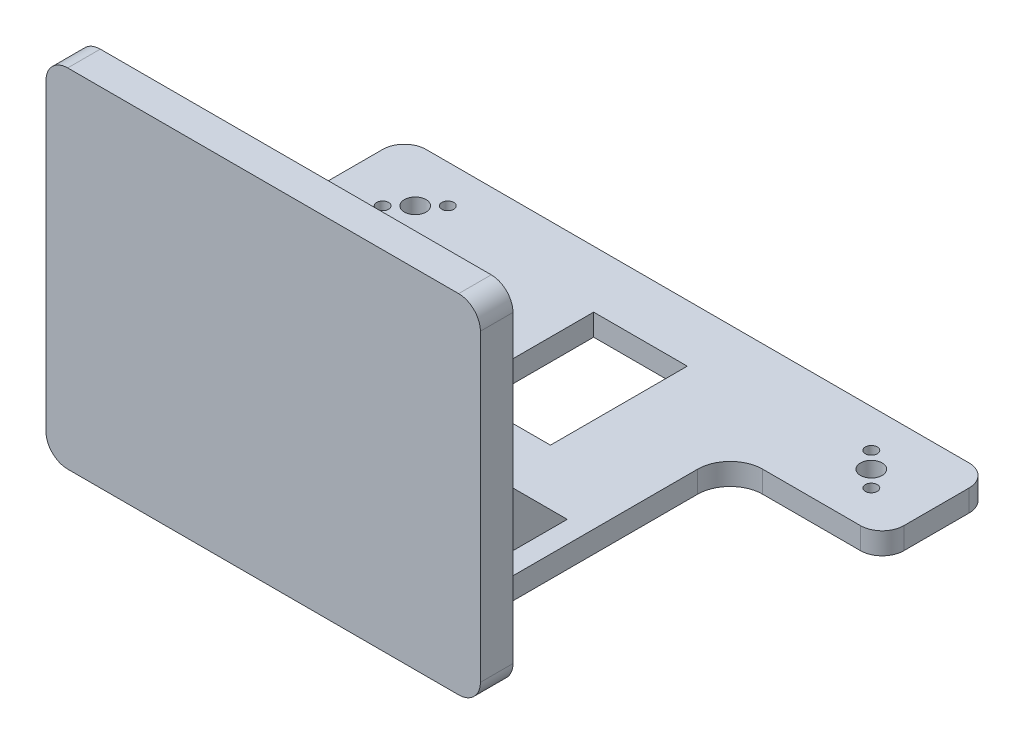
SolidWorks part; units mm, degrees
ref_plane "Vorne" through (0, 0, 0) normal (0, 0, 1) x (1, 0, 0)
ref_plane "Oben" through (0, 0, 0) normal (0, 1, 0) x (1, 0, 0)
ref_plane "Rechts" through (0, 0, 0) normal (1, 0, 0) x (0, 0, -1)
ref_plane "E_Boden" through (0, 1, 0) normal (0, 1, 0) x (1, 0, 0)
sketch "Skizze1" plane through (0, 0, 0) normal (0, 1, 0) x (1, 0, 0)
  line L0 (0, -133.037) -> (0, 127.1868) construction
  line L1 (-165.4867, 0) -> (188.3198, 0) construction
  line L2 (-125, 100) -> (125, 100)
  line L3 (-135, 90) -> (-135, 60)
  line L8 (-125, 50) -> (-80, 50)
  line L9 (-65, 35) -> (-65, -70)
  line L10 (-80, -85) -> (-90, -85)
  line L12 (-80, -100) -> (80, -100)
  line L14 (80, -85) -> (90, -85)
  line L15 (65, 35) -> (65, -70)
  line L16 (125, 50) -> (80, 50)
  line L17 (135, 90) -> (135, 60)
  line L18 (0, 75) -> (-166.9097, 75) construction
  line L19 (0, 82.5) -> (-150.2601, 82.5) construction
  line L20 (0, 67.5) -> (-143.7021, 67.5) construction
  line L21 (-112.5, 67.5) -> (-112.5, 109.8946) construction
  line L22 (-97.5, 82.5) -> (-97.5, 110.5565) construction
  line L23 (-105, 75) -> (-105, 35) construction
  line L24 (-105, 35) -> (-105, 140.5126) construction
  line L25 (-21.55, 73.71) -> (21.55, 73.71)
  line L26 (21.55, 73.71) -> (21.55, 10.71)
  line L27 (21.55, 10.71) -> (-21.55, 10.71)
  line L28 (-21.55, 10.71) -> (-21.55, 73.71)
  line L29 (0, 42.21) -> (-56.3168, 42.21) construction
  line L30 (-56.3168, 42.21) -> (55.721, 42.21) construction
  line L32 (-100, -100) -> (-80, -100)
  line L33 (80, -100) -> (100, -100)
  line L35 (-90, -85) -> (-100, -85)
  line L37 (90, -85) -> (100, -85)
  line L39 (-100, -85) -> (-100, -100)
  line L40 (100, -85) -> (100, -100)
  arc A0 (65, 35) -> (80, 50) centre (80, 35) cw
  arc A1 (80, -85) -> (65, -70) centre (80, -70) cw
  arc A2 (-65, -70) -> (-80, -85) centre (-80, -70) cw
  arc A3 (-80, 50) -> (-65, 35) centre (-80, 35) cw
  arc A8 (-135, 60) -> (-125, 50) centre (-125, 60) ccw
  arc A9 (125, 50) -> (135, 60) centre (125, 60) ccw
  arc A10 (135, 90) -> (125, 100) centre (125, 90) ccw
  arc A11 (-125, 100) -> (-135, 90) centre (-125, 90) ccw
  circle A12 centre (-105, 75) radius 5
  circle A13 centre (105, 75) radius 5
  circle A14 centre (-97.5, 82.5) radius 2.75
  circle A15 centre (-112.5, 67.5) radius 2.75
  circle A16 centre (97.5, 82.5) radius 2.75
  circle A17 centre (112.5, 67.5) radius 2.75
  point P6 (-99.7669, 90)
  point P15 (0, -100)
  point P16 (0, 100)
  point P22 (65, 50)
  point P25 (65, -85)
  point P28 (-65, -85)
  point P31 (-65, 50)
  point P34 (100, -85)
  point P37 (100, -100)
  point P40 (-100, -100)
  point P43 (-100, -85)
  point P46 (-135, 50)
  point P49 (135, 50)
  point P52 (135, 100)
  point P55 (-135, 100)
  point P77 (0, 42.21)
  dimension "D7" = 15
  dimension "D8" = 10
  dimension "D9" = 10
  dimension "D13" = 5.5
  dimension "D14" = 5.5
  dimension "D1" = 270
  dimension "D2" = 50
  dimension "D3" = 150
  dimension "D4" = 200
  dimension "D5" = 130
  dimension "D6" = 15
  dimension "D10" = 210
  dimension "D11" = 15
  dimension "D12" = 7.5
  dimension "D15" = 15
  dimension "D16" = 7.5
  dimension "D17" = 32.79
  dimension "D18" = 43.1
  dimension "D19" = 63
extrude "Aufsatz-Linear austragen1" add sketch "Skizze1" along normal blind 10
sketch "Skizze2" plane through (0, 10, 0) normal (0, 1, 0) x (1, 0, 0)
sketch "Skizze3" plane through (0, 10, 0) normal (0, 1, 0) x (1, 0, 0)
  line L1 (-100, -85) -> (100, -85)
  line L2 (-100, -85) -> (-100, -100)
  line L3 (-100, -100) -> (100, -100)
  line L4 (100, -85) -> (100, -100)
extrude "Aufsatz-Linear austragen2" add sketch "Skizze3" along normal blind 150
fillet "Verrundung1" radius 10 4 edges at (100, 0, 92.5) (-100, 0, 92.5) (-100, 160, 92.5) (100, 160, 92.5)
ref_plane "Ebene1" through (-50, 0, 0) normal (-1, 0, 0) x (0, 0, 1)
sketch "Skizze5" plane through (-50, 0, 0) normal (-1, 0, 0) x (0, 0, 1)
  line L0 (15, 10) -> (85, 80)
  line L1 (-35, 10) -> (70, 10) construction
  line L2 (85, 150) -> (85, 10) construction
  line L3 (85, 80) -> (85, 10)
  line L4 (85, 10) -> (15, 10)
  dimension "D1" = 70
  dimension "D2" = 70
extrude "Aufsatz-Linear austragen3" add sketch "Skizze5" against normal blind 10
ref_plane "Ebene2" through (55, 0, 0) normal (1, 0, 0) x (0, 0, -1)
sketch "Skizze6" plane through (55, 0, 0) normal (1, 0, 0) x (0, 0, -1)
  line L0 (-15, 10) -> (-85, 80)
  line L1 (-85, 150) -> (-85, 10) construction
  line L2 (-85, 80) -> (-85, 10)
  line L3 (-85, 10) -> (-15, 10)
extrude "Aufsatz-Linear austragen4" add sketch "Skizze6" against normal blind 10
sketch "Skizze7" plane through (0, 10, 0) normal (0, 1, 0) x (1, 0, 0)
  line L0 (0, 73.71) -> (0, 10.71) construction
  line L1 (21.55, 73.71) -> (-21.55, 73.71) construction
  line L2 (-21.55, 10.71) -> (21.55, 10.71) construction
  line L3 (-21.55, 42.21) -> (21.55, 42.21) construction
  line L4 (-21.55, 73.71) -> (-21.55, 10.71) construction
  line L5 (21.55, 10.71) -> (21.55, 73.71) construction
  line L6 (-105, 58) -> (0, 25.21)
  line L7 (-105, 92) -> (4.9584, 58.4708)
  circle A0 centre (-105, 75) radius 17
  circle A1 centre (0, 42.21) radius 17
  dimension "D1" = 34
  dimension "D2" = 34
